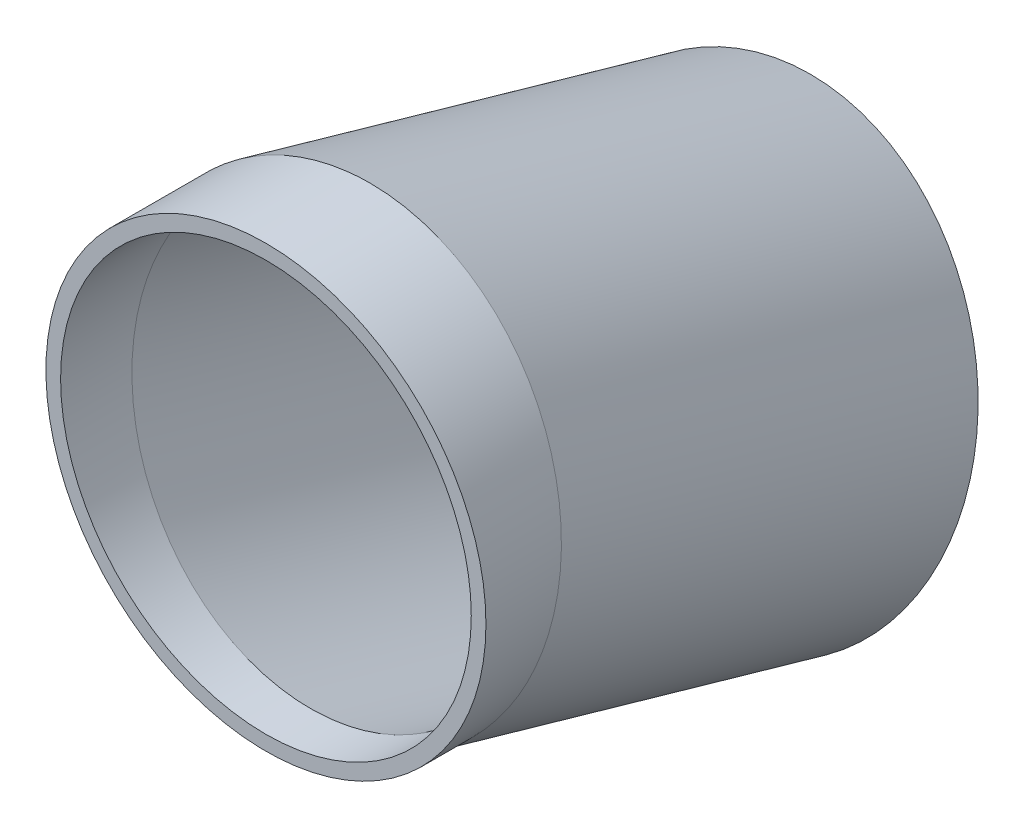
SolidWorks part; units mm, degrees
material "Plain Carbon Steel"
ref_plane "Front Plane" through (0, 0, 0) normal (0, 0, 1) x (1, 0, 0)
ref_plane "Top Plane" through (0, 0, 0) normal (0, 1, 0) x (1, 0, 0)
ref_plane "Right Plane" through (0, 0, 0) normal (1, 0, 0) x (0, 0, -1)
sketch "Sketch1" plane through (0, 0, 0) normal (0, 0, 1) x (1, 0, 0)
  circle A0 centre (0, 0) radius 70
  circle A1 centre (0, 0) radius 75
  dimension "D1" = 150
  dimension "D2" = 140
sketch "Sketch2" plane through (0, 0, 0) normal (1, 0, 0) x (0, 0, -1)
  line L0 (0, 0) -> (25, 0)
  line L1 (25, 0) -> (165, -40)
  dimension "D1" = 25
  dimension "D2" = 140
  dimension "D3" = 40
sweep "Sweep1" add profiles "Sketch1" path "Sketch2"
